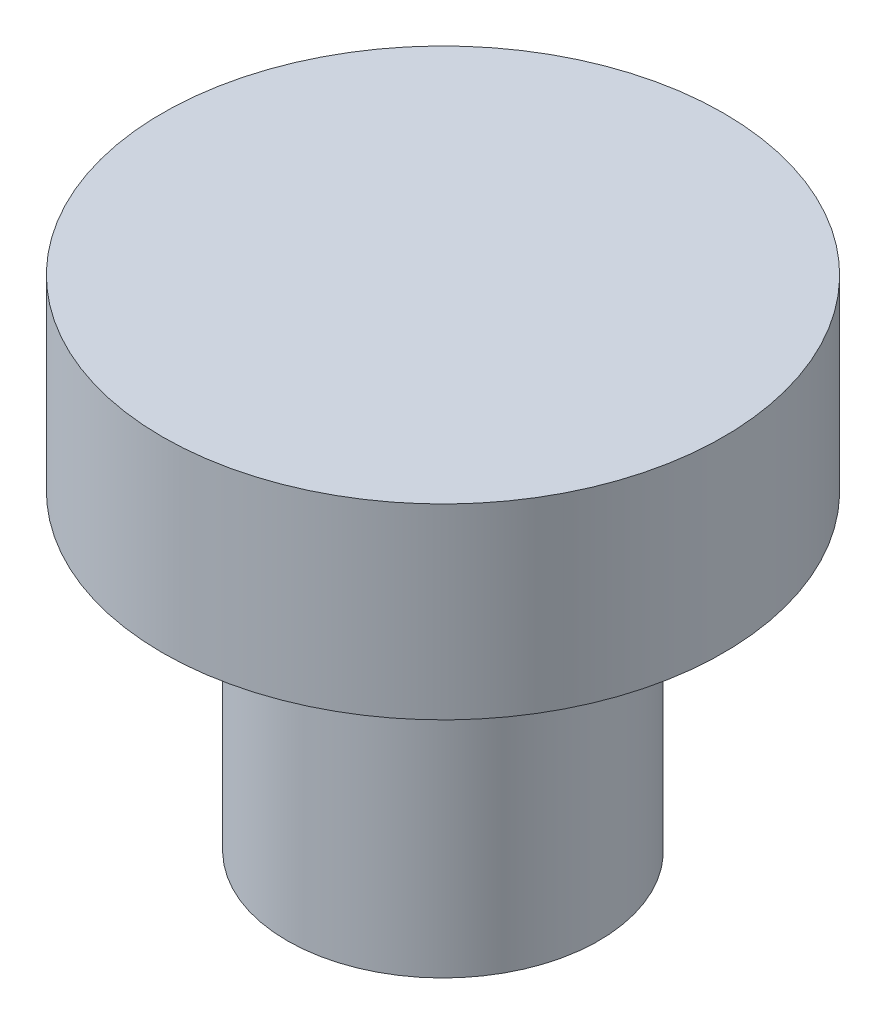
SolidWorks part; units mm, degrees
ref_plane "Front Plane" through (0, 0, 0) normal (0, 0, 1) x (1, 0, 0)
ref_plane "Top Plane" through (0, 0, 0) normal (0, 1, 0) x (1, 0, 0)
ref_plane "Right Plane" through (0, 0, 0) normal (1, 0, 0) x (0, 0, -1)
other "Configuration Table"
sketch "Sketch1" plane through (0, 0, 0) normal (0, 1, 0) x (1, 0, 0)
  circle A0 centre (0, 0) radius 4.5
  dimension "D1" = 9
extrude "Head" add sketch "Sketch1" along normal blind 3
sketch "Sketch2" plane through (0, 0, 0) normal (0, 1, 0) x (1, 0, 0)
  circle A0 centre (0, 0) radius 2.5
  dimension "D1" = 5
extrude "Thread" add sketch "Sketch2" along normal blind 5 from offset 5
equation "\"Jar_OD\"= 90  'ASSUMED - Part G fallback - jar outer diameter"
equation "\"Jar_H\"= 120  'ASSUMED - Part G fallback - jar height"
equation "\"Pump_L\"= 45  'ASSUMED - Part G fallback"
equation "\"Pump_W\"= 24  'ASSUMED - Part G fallback"
equation "\"Pump_H\"= 33  'ASSUMED - Part G fallback"
equation "\"Pump_Outlet_OD\"= 7.5  'ASSUMED - Part G fallback"
equation "\"Tube_OD\"= 8  'ASSUMED - Part G fallback"
equation "\"Tube_ID\"= 6  'ASSUMED - Part G fallback"
equation "\"TDS_Body_Dia\"= 12  'ASSUMED - Part G fallback"
equation "\"TDS_Wet_Len\"= 45  'ASSUMED - Part G fallback - length in water"
equation "\"DS_Tube_Dia\"= 6  'ASSUMED - Part G fallback"
equation "\"DS_Tube_Len\"= 50  'ASSUMED - Part G fallback"
equation "\"ORP_Body_Dia\"= 12  'ASSUMED - Part G fallback"
equation "\"ORP_Body_Len\"= 150  'ASSUMED - Part G fallback"
equation "\"ORP_Cap_Dia\"= 16  'ASSUMED - Part G fallback"
equation "\"Turb_W\"= 33  'ASSUMED - Part G fallback - head width"
equation "\"Turb_D\"= 28  'ASSUMED - Part G fallback - head depth"
equation "\"Turb_H\"= 30  'ASSUMED - Part G fallback - head height"
equation "\"Turb_Slot_W\"= 10  'ASSUMED - Part G fallback - slot width"
equation "\"Flow_L\"= 62  'ASSUMED - Part G fallback YF-S201"
equation "\"Flow_W\"= 36  'ASSUMED - Part G fallback"
equation "\"Flow_H\"= 35  'ASSUMED - Part G fallback"
equation "\"Thread_G12_OD\"= 20.955  'ASSUMED - Part G fallback thread G1/2 (major diameter)"
equation "\"Valve_L\"= 75  'ASSUMED - Part G fallback"
equation "\"Valve_W\"= 45  'ASSUMED - Part G fallback"
equation "\"Valve_H\"= 60  'ASSUMED - Part G fallback"
equation "\"Tee_L\"= 40  'ASSUMED - Part G fallback - overall length"
equation "\"Tee_Branch_L\"= 25  'ASSUMED - Part G fallback"
equation "\"Tee_OD\"= 12  'ASSUMED - Part G fallback"
equation "\"LED_Board_L\"= 20  'ASSUMED - Part G fallback"
equation "\"LED_Board_W\"= 20  'ASSUMED - Part G fallback - LED at centre"
equation "\"GUVA_L\"= 20  'ASSUMED - Part G fallback"
equation "\"GUVA_W\"= 12  'ASSUMED - Part G fallback - sensor at centre"
equation "\"Reed_L\"= 27  'ASSUMED - Part G fallback MC-38 half"
equation "\"Reed_W\"= 14  'ASSUMED - Part G fallback"
equation "\"Reed_H\"= 8  'ASSUMED - Part G fallback"
equation "\"ESP_L\"= 51  'ASSUMED - Part G fallback"
equation "\"ESP_W\"= 28  'ASSUMED - Part G fallback"
equation "\"TFT_L\"= 58  'ASSUMED - Part G fallback - board"
equation "\"TFT_W\"= 35  'ASSUMED - Part G fallback - board"
equation "\"TFT_Win_L\"= 35  'ASSUMED - Part G fallback - visible window"
equation "\"TFT_Win_W\"= 28  'ASSUMED - Part G fallback - visible window"
equation "\"Relay_L\"= 50  'ASSUMED - Part G fallback"
equation "\"Relay_W\"= 26  'ASSUMED - Part G fallback"
equation "\"Relay_H\"= 19  'ASSUMED - Part G fallback"
equation "\"Mosfet_L\"= 34  'ASSUMED - Part G fallback"
equation "\"Mosfet_W\"= 17  'ASSUMED - Part G fallback"
equation "\"Mosfet_H\"= 12  'ASSUMED - Part G fallback"
equation "\"TDS_Board_L\"= 42  'ASSUMED - Part G fallback"
equation "\"TDS_Board_W\"= 32  'ASSUMED - Part G fallback"
equation "\"Turb_Board_L\"= 38  'ASSUMED - Part G fallback"
equation "\"Turb_Board_W\"= 28  'ASSUMED - Part G fallback"
equation "\"BNC_Thread_Dia\"= 9.5  'ASSUMED - Part G fallback"
equation "\"Plate_L\"= 420  'ASSUMED - Part G fallback"
equation "\"Plate_W\"= 297  'ASSUMED - Part G fallback"
equation "\"Plate_T\"= 6  'ASSUMED - Part G fallback"
equation "\"Booster_L\"= 150  'ASSUMED - Part G fallback - booster pump"
equation "\"Booster_W\"= 95  'ASSUMED - Part G fallback"
equation "\"Booster_H\"= 100  'ASSUMED - Part G fallback"
equation "\"PTube_OD\"= 6.35  'ASSUMED - Part G fallback - product tube 1/4 inch"
equation "\"Qz_Out\"= 12  'ASSUMED - Part G fallback - quartz channel outside square"
equation "\"Qz_Path\"= 10  'ASSUMED - Part G fallback - quartz channel inside light path"
equation "\"Qz_L\"= 40  'ASSUMED - Part G fallback - quartz channel length"
equation "\"LED860_Dia\"= 5  'ASSUMED - Part G fallback - 860 nm LED"
equation "\"BPW_L\"= 5.4  'ASSUMED - Part G fallback - BPW34"
equation "\"BPW_W\"= 4.3  'ASSUMED - Part G fallback - BPW34"
equation "\"Cart_Dia\"= 50  'ASSUMED - Part G fallback - sediment and pre-carbon cartridges"
equation "\"Cart_L\"= 255  'ASSUMED - Part G fallback"
equation "\"UF_Dia\"= 50  'ASSUMED - Part G fallback - UF cartridge"
equation "\"UF_L\"= 260  'ASSUMED - Part G fallback"
equation "\"RO_Dia\"= 62  'ASSUMED - Part G fallback - RO membrane housing"
equation "\"RO_L\"= 300  'ASSUMED - Part G fallback"
equation "\"UVC_Dia\"= 40  'ASSUMED - Part G fallback - UV-C chamber"
equation "\"UVC_L\"= 300  'ASSUMED - Part G fallback"
equation "\"Tank_W\"= 260  'ASSUMED - Part G fallback - storage tank"
equation "\"Tank_D\"= 160  'ASSUMED - Part G fallback"
equation "\"Tank_H\"= 300  'ASSUMED - Part G fallback"
equation "\"Cab_W\"= 400  'ASSUMED - Part G fallback - purifier cabinet"
equation "\"Cab_D\"= 270  'ASSUMED - Part G fallback"
equation "\"Cab_H\"= 560  'ASSUMED - Part G fallback"
equation "\"ORP_Board_L\"= 40  'ASSUMED - Part G fallback - ORP buffer board"
equation "\"ORP_Board_W\"= 30  'ASSUMED - Part G fallback"
equation "\"Opt_Board_L\"= 50  'ASSUMED - Part G fallback - optical front-end board"
equation "\"Opt_Board_W\"= 40  'ASSUMED - Part G fallback"
equation "\"Buck_L\"= 43  'ASSUMED - Part G fallback - 12 V to 5 V buck module"
equation "\"Buck_W\"= 21  'ASSUMED - Part G fallback"
equation "\"Buck_H\"= 14  'ASSUMED - Part G fallback"
equation "\"BB_L\"= 165  'ASSUMED - Part G fallback - breadboard (As_Built_R3 only)"
equation "\"BB_W\"= 55  'ASSUMED - Part G fallback"
equation "\"BB_H\"= 10  'ASSUMED - Part G fallback"
equation "\"Cuv_W\"= 12.5  'ASSUMED - old R3 cuvette (station suppressed in SS4)"
equation "\"Cuv_D\"= 12.5  'ASSUMED - old R3 cuvette (station suppressed in SS4)"
equation "\"Cuv_H\"= 45  'ASSUMED - old R3 cuvette (station suppressed in SS4)"
equation "\"Probe_Clr\"= 0.3  'DESIGN VALUE - Part C rule 3 - printed probe hole = diameter + 0.3"
equation "\"Label_H\"= 0.6  'DESIGN VALUE - Part D - raised label height"
